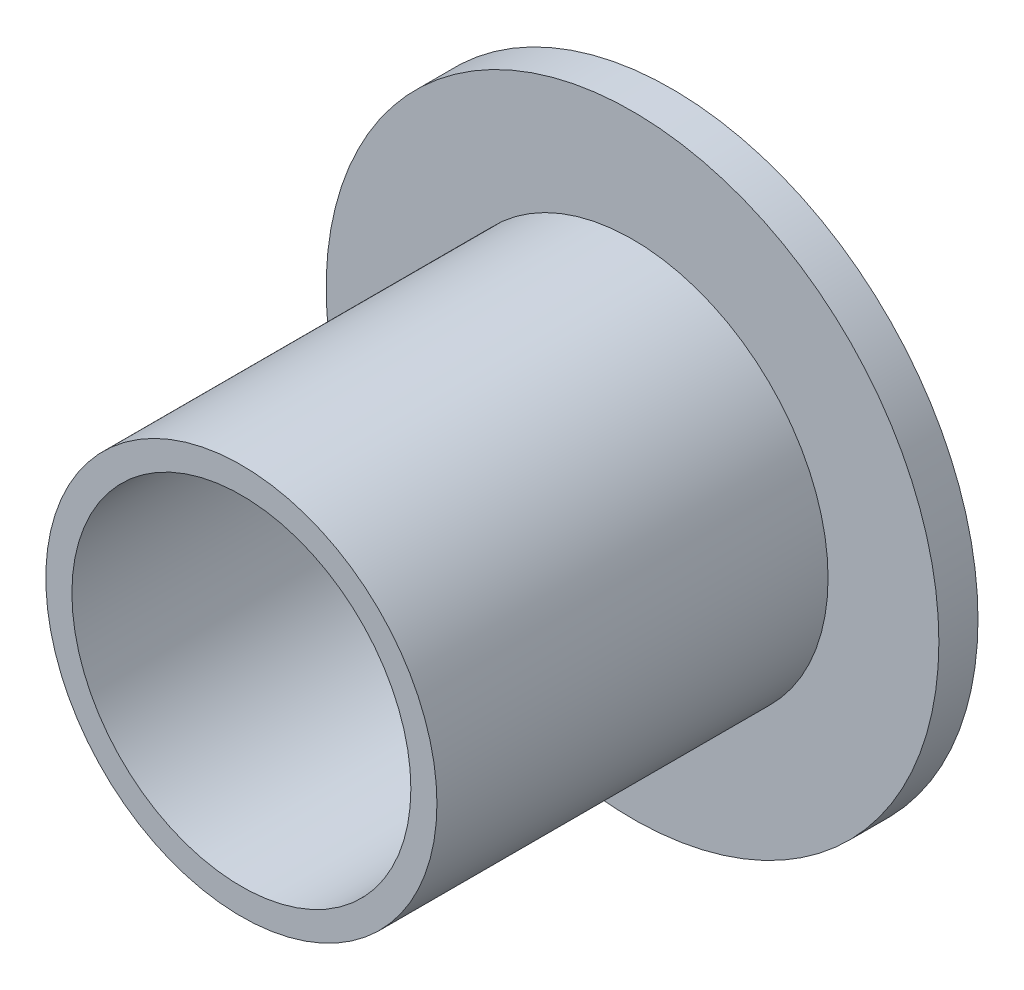
SolidWorks part; units mm, degrees
ref_plane "Front Plane" through (0, 0, 0) normal (0, 0, 1) x (1, 0, 0)
ref_plane "Top Plane" through (0, 0, 0) normal (0, 1, 0) x (1, 0, 0)
ref_plane "Right Plane" through (0, 0, 0) normal (1, 0, 0) x (0, 0, -1)
sketch "Sketch1" plane through (0, 0, 0) normal (0, 0, 1) x (1, 0, 0)
  circle A0 centre (0, 0) radius 23.5
  dimension "D1" = 47
extrude "Boss-Extrude1" add sketch "Sketch1" along normal blind 3
sketch "Sketch2" plane through (0, 0, 3) normal (0, 0, 1) x (1, 0, 0)
  circle A0 centre (0, 0) radius 15
  dimension "D1" = 30
extrude "Boss-Extrude2" add sketch "Sketch2" along normal blind 30
sketch "Sketch3" plane through (0, 0, 33) normal (0, 0, 1) x (1, 0, 0)
  circle A0 centre (0, 0) radius 13
  dimension "D1" = 26
extrude "Cut-Extrude1" cut sketch "Sketch3" against normal through all
